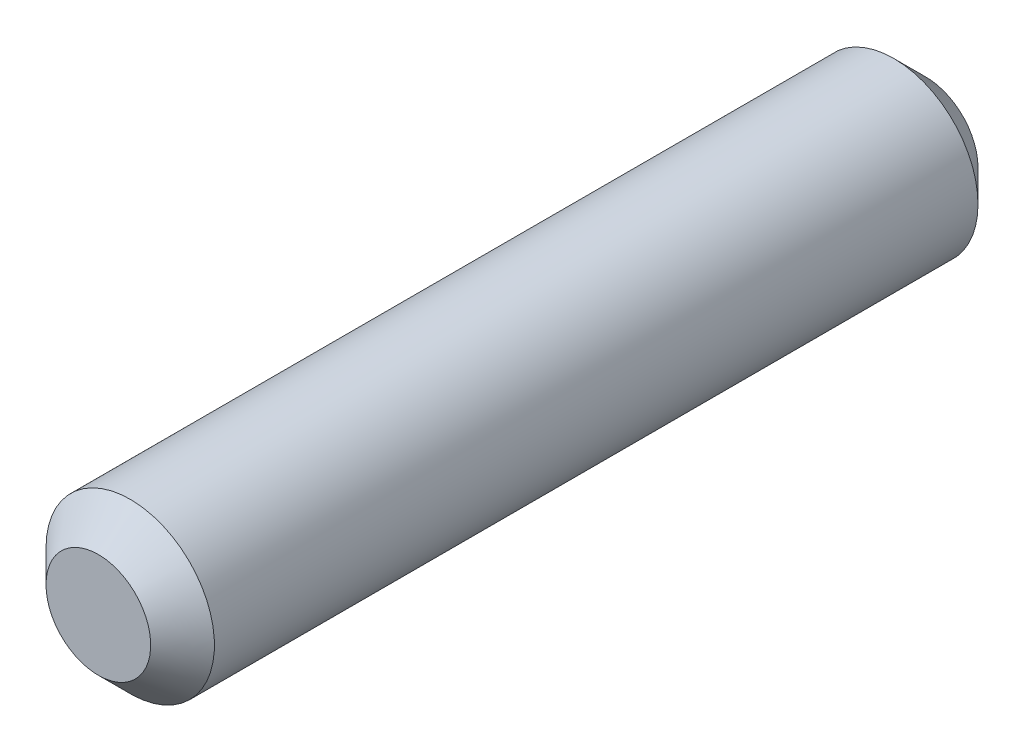
SolidWorks part; units mm, degrees
ref_plane "Front Plane" through (0, 0, 0) normal (0, 0, 1) x (1, 0, 0)
ref_plane "Top Plane" through (0, 0, 0) normal (0, 1, 0) x (1, 0, 0)
ref_plane "Right Plane" through (0, 0, 0) normal (1, 0, 0) x (0, 0, -1)
sketch "Sketch1" plane through (0, 0, 0) normal (0, 0, 1) x (1, 0, 0)
  circle A0 centre (0, 0) radius 1.585
  dimension "D1" = 3.17
extrude "Boss-Extrude1" add sketch "Sketch1" along normal mid plane 15.57
chamfer "Chamfer1" distance 0.6 angle 45 2 edges at (1.585, 0, -7.785) (1.585, 0, 7.785)
